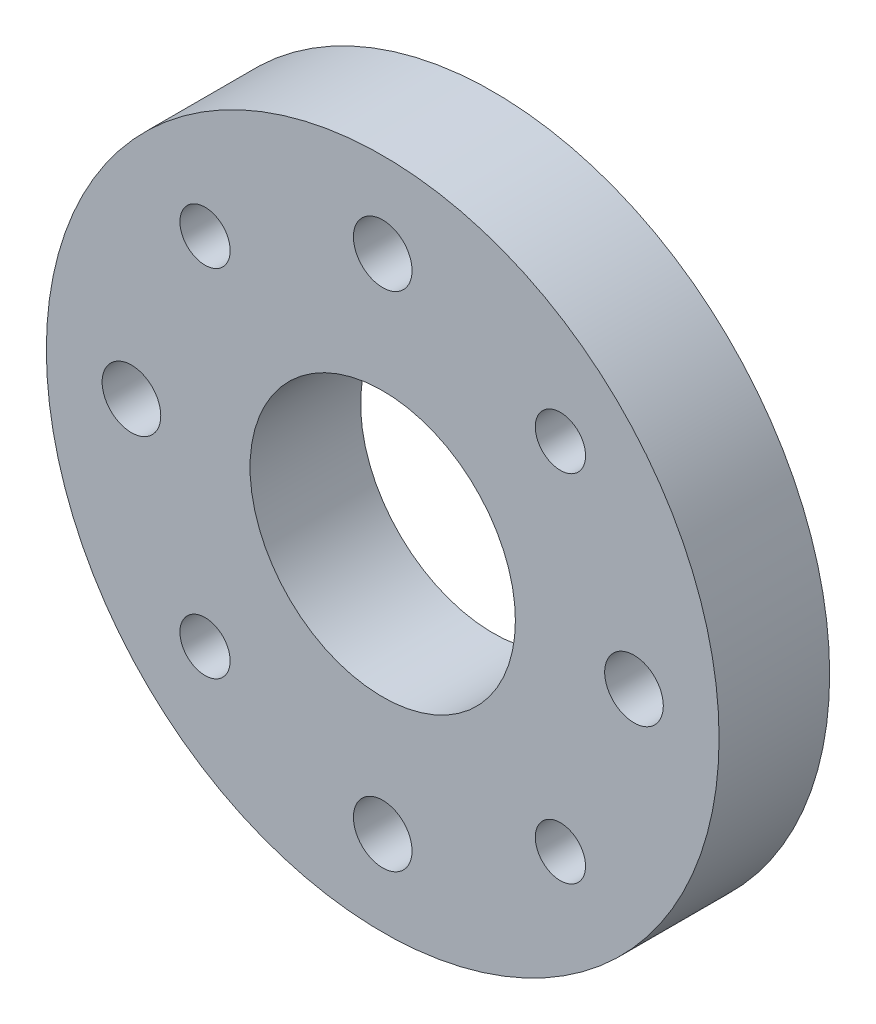
SolidWorks part; units mm, degrees
material "Balsa"
ref_plane "Front Plane" through (0, 0, 0) normal (0, 0, 1) x (1, 0, 0)
ref_plane "Top Plane" through (0, 0, 0) normal (0, 1, 0) x (1, 0, 0)
ref_plane "Right Plane" through (0, 0, 0) normal (1, 0, 0) x (0, 0, -1)
sketch "Sketch1" plane through (0, 0, 0) normal (0, 0, 1) x (1, 0, 0)
  circle A1 centre (0, 0) radius 8
  circle A2 centre (0, 0) radius 15 construction
  circle A3 centre (0, 15) radius 1.75
  circle A4 centre (10.6066, 10.6066) radius 1.5
  circle A5 centre (15, 0) radius 1.75
  circle A6 centre (10.6066, -10.6066) radius 1.5
  circle A7 centre (0, -15) radius 1.75
  circle A8 centre (-10.6066, -10.6066) radius 1.5
  circle A9 centre (-15, 0) radius 1.75
  circle A10 centre (-10.6066, 10.6066) radius 1.5
  circle A11 centre (0, 0) radius 20
  dimension "D1" = 40
  dimension "D2" = 16
  dimension "D3" = 30
  dimension "D4" = 3.5
  dimension "D5" = 3
  dimension "D6" = 45
  dimension "D7" = 4
extrude "Boss-Extrude1" add sketch "Sketch1" along normal blind 6.6
other "Move Face1" face at (8, 0, 6.6) face at (20, 0, 6.6) parameters "D1"=0.08
